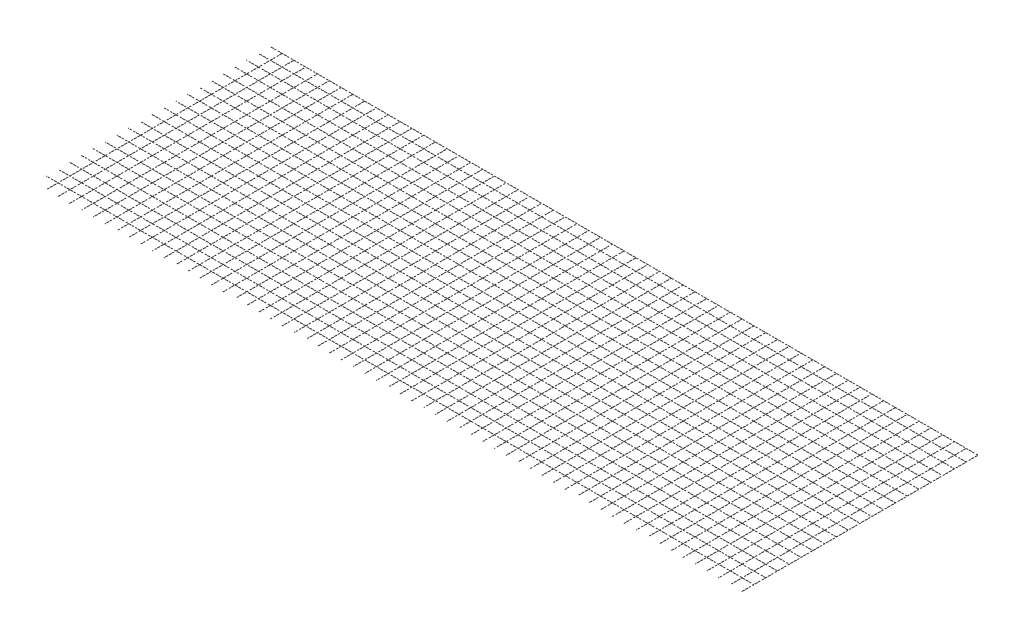
SolidWorks part; units mm, degrees
ref_plane "Front Plane" through (0, 0, 0) normal (0, 0, 1) x (1, 0, 0)
ref_plane "Top Plane" through (0, 0, 0) normal (0, 1, 0) x (1, 0, 0)
ref_plane "Right Plane" through (0, 0, 0) normal (1, 0, 0) x (0, 0, -1)
sketch "Sketch2" plane through (0, 0, 0) normal (0, 0, 1) x (1, 0, 0)
  line L0 (55, 0) -> (-55, 0) construction
  circle A0 centre (2815.8185, 0) radius 0.5
  circle A1 centre (2915.8185, 0) radius 0.5
  circle A2 centre (3015.8185, 0) radius 0.5
  circle A3 centre (3115.8185, 0) radius 0.5
  circle A4 centre (3215.8185, 0) radius 0.5
  circle A5 centre (3315.8185, 0) radius 0.5
  circle A6 centre (3415.8185, 0) radius 0.5
  circle A7 centre (3515.8185, 0) radius 0.5
  circle A8 centre (3615.8185, 0) radius 0.5
  circle A9 centre (3715.8185, 0) radius 0.5
  circle A10 centre (3815.8185, 0) radius 0.5
  circle A11 centre (3915.8185, 0) radius 0.5
  circle A12 centre (4015.8185, 0) radius 0.5
  circle A13 centre (4115.8185, 0) radius 0.5
  circle A14 centre (4215.8185, 0) radius 0.5
  circle A15 centre (4315.8185, 0) radius 0.5
  circle A16 centre (4415.8185, 0) radius 0.5
  circle A17 centre (4515.8185, 0) radius 0.5
  circle A18 centre (4615.8185, 0) radius 0.5
  circle A19 centre (4715.8185, 0) radius 0.5
  circle A20 centre (4815.8185, 0) radius 0.5
  circle A21 centre (4915.8185, 0) radius 0.5
  circle A22 centre (5015.8185, 0) radius 0.5
  circle A23 centre (5115.8185, 0) radius 0.5
  circle A24 centre (5215.8185, 0) radius 0.5
  circle A25 centre (5315.8185, 0) radius 0.5
  circle A26 centre (5415.8185, 0) radius 0.5
  circle A27 centre (5515.8185, 0) radius 0.5
  circle A28 centre (5615.8185, 0) radius 0.5
  circle A29 centre (5715.8185, 0) radius 0.5
  circle A30 centre (5815.8185, 0) radius 0.5
  circle A31 centre (5915.8185, 0) radius 0.5
  circle A32 centre (6015.8185, 0) radius 0.5
  circle A33 centre (6115.8185, 0) radius 0.5
  circle A34 centre (6215.8185, 0) radius 0.5
  circle A35 centre (6315.8185, 0) radius 0.5
  circle A36 centre (6415.8185, 0) radius 0.5
  circle A37 centre (6515.8185, 0) radius 0.5
  circle A38 centre (6615.8185, 0) radius 0.5
  circle A39 centre (6715.8185, 0) radius 0.5
  circle A40 centre (6815.8185, 0) radius 0.5
  circle A41 centre (6915.8185, 0) radius 0.5
  circle A42 centre (7015.8185, 0) radius 0.5
  circle A43 centre (7115.8185, 0) radius 0.5
  circle A44 centre (7215.8185, 0) radius 0.5
  circle A45 centre (7315.8185, 0) radius 0.5
  circle A46 centre (7415.8185, 0) radius 0.5
  circle A47 centre (7515.8185, 0) radius 0.5
  circle A48 centre (7615.8185, 0) radius 0.5
  circle A49 centre (7715.8185, 0) radius 0.5
  circle A50 centre (7815.8185, 0) radius 0.5
  circle A51 centre (7915.8185, 0) radius 0.5
  circle A52 centre (8015.8185, 0) radius 0.5
  circle A53 centre (8115.8185, 0) radius 0.5
  circle A54 centre (8215.8185, 0) radius 0.5
  circle A55 centre (8315.8185, 0) radius 0.5
  circle A56 centre (8415.8185, 0) radius 0.5
  circle A57 centre (8515.8185, 0) radius 0.5
  circle A58 centre (8615.8185, 0) radius 0.5
  circle A59 centre (8715.8185, 0) radius 0.5
  dimension "D1" = 60
extrude "Boss-Extrude2" add sketch "Sketch2" along normal blind 2000
ref_plane "Plane1" through (8715.3185, 0, 0) normal (-1, 0, 0) x (0, 0, 1)
sketch "Sketch3" plane through (8715.3185, 0, 0) normal (-1, 0, 0) x (0, 0, 1)
  circle A0 centre (0.5, 1) radius 0.5
  circle A1 centre (100.5, 1) radius 0.5
  circle A2 centre (200.5, 1) radius 0.5
  circle A3 centre (300.5, 1) radius 0.5
  circle A4 centre (400.5, 1) radius 0.5
  circle A5 centre (500.5, 1) radius 0.5
  circle A6 centre (600.5, 1) radius 0.5
  circle A7 centre (700.5, 1) radius 0.5
  circle A8 centre (800.5, 1) radius 0.5
  circle A9 centre (900.5, 1) radius 0.5
  circle A10 centre (1000.5, 1) radius 0.5
  circle A11 centre (1100.5, 1) radius 0.5
  circle A12 centre (1200.5, 1) radius 0.5
  circle A13 centre (1300.5, 1) radius 0.5
  circle A14 centre (1400.5, 1) radius 0.5
  circle A15 centre (1500.5, 1) radius 0.5
  circle A16 centre (1600.5, 1) radius 0.5
  circle A17 centre (1700.5, 1) radius 0.5
  circle A18 centre (1800.5, 1) radius 0.5
  circle A19 centre (1900.5, 1) radius 0.5
  dimension "D1" = 20
extrude "Boss-Extrude3" add sketch "Sketch3" along normal blind 6000 separate body
